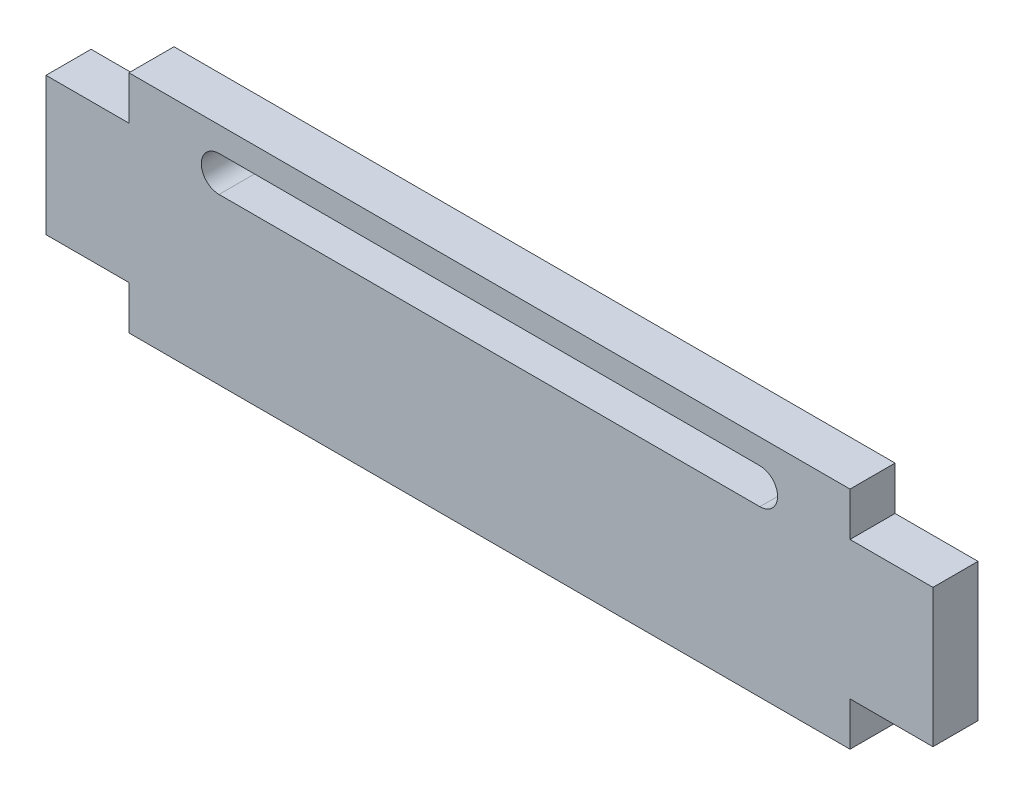
SolidWorks part; units mm, degrees
ref_plane "Front Plane" through (0, 0, 0) normal (0, 0, 1) x (1, 0, 0)
ref_plane "Top Plane" through (0, 0, 0) normal (0, 1, 0) x (1, 0, 0)
ref_plane "Right Plane" through (0, 0, 0) normal (1, 0, 0) x (0, 0, -1)
sketch "Sketch1" plane through (0, 0, 0) normal (0, 0, 1) x (1, 0, 0)
  line L0 (25.4, 0) -> (-25.4, 0) construction
  line L1 (-25.4, -7.9375) -> (25.4, -7.9375)
  line L2 (0, 7.9375) -> (0, -7.9375) construction
  line L3 (-25.4, 7.9375) -> (25.4, 7.9375)
  line L4 (25.4, -7.9375) -> (25.4, -4.8625)
  line L5 (-25.4, -7.9375) -> (25.4, 7.9375) construction
  line L6 (-25.4, 7.9375) -> (25.4, -7.9375) construction
  line L7 (25.4, 4.8625) -> (25.4, 7.9375)
  line L8 (31.242, -4.8625) -> (25.4, -4.8625)
  line L9 (31.242, -4.8625) -> (31.242, 4.8625)
  line L10 (31.242, 4.8625) -> (25.4, 4.8625)
  line L11 (-31.242, 4.8625) -> (-25.4, -4.8625) construction
  line L12 (31.242, -4.8625) -> (25.4, 4.8625) construction
  line L13 (31.242, 4.8625) -> (25.4, -4.8625) construction
  line L14 (-31.242, -4.8625) -> (-25.4, 4.8625) construction
  line L15 (-31.242, 4.8625) -> (-25.4, 4.8625)
  line L16 (-31.242, -4.8625) -> (-31.242, 4.8625)
  line L17 (-31.242, -4.8625) -> (-25.4, -4.8625)
  line L18 (-25.4, 4.8625) -> (-25.4, 7.9375)
  line L19 (-25.4, -7.9375) -> (-25.4, -4.8625)
  line L20 (-10, -3.175) -> (-10, -3.125) construction
  line L21 (-19.05, 4.9375) -> (19.05, 4.9375) construction
  line L22 (10, 3.125) -> (10, 3.175) construction
  line L23 (10, -3.175) -> (10, -3.125) construction
  line L24 (-19.05, 6.1875) -> (19.05, 6.1875)
  line L25 (-19.05, 3.6875) -> (19.05, 3.6875)
  line L27 (-10, 3.125) -> (-10, 3.175) construction
  arc A0 (-19.05, 6.1875) -> (-19.05, 3.6875) centre (-19.05, 4.9375) ccw
  arc A1 (19.05, 3.6875) -> (19.05, 6.1875) centre (19.05, 4.9375) ccw
  point P0 (0, 0)
  point P8 (28.321, 0)
  point P19 (-28.321, 0)
  point P22 (-10, 0)
  point P29 (10, 0)
  point P30 (0, 4.9375)
  dimension "D5" = 1.25
  dimension "D1" = 50.8
  dimension "D2" = 15.875
  dimension "D3" = 5.842
  dimension "D4" = 9.725
  dimension "D6" = 6.35
  dimension "D7" = 10
  dimension "D8" = 38.1
  dimension "D9" = 3
extrude "Boss-Extrude1" add sketch "Sketch1" along normal blind 3.175
